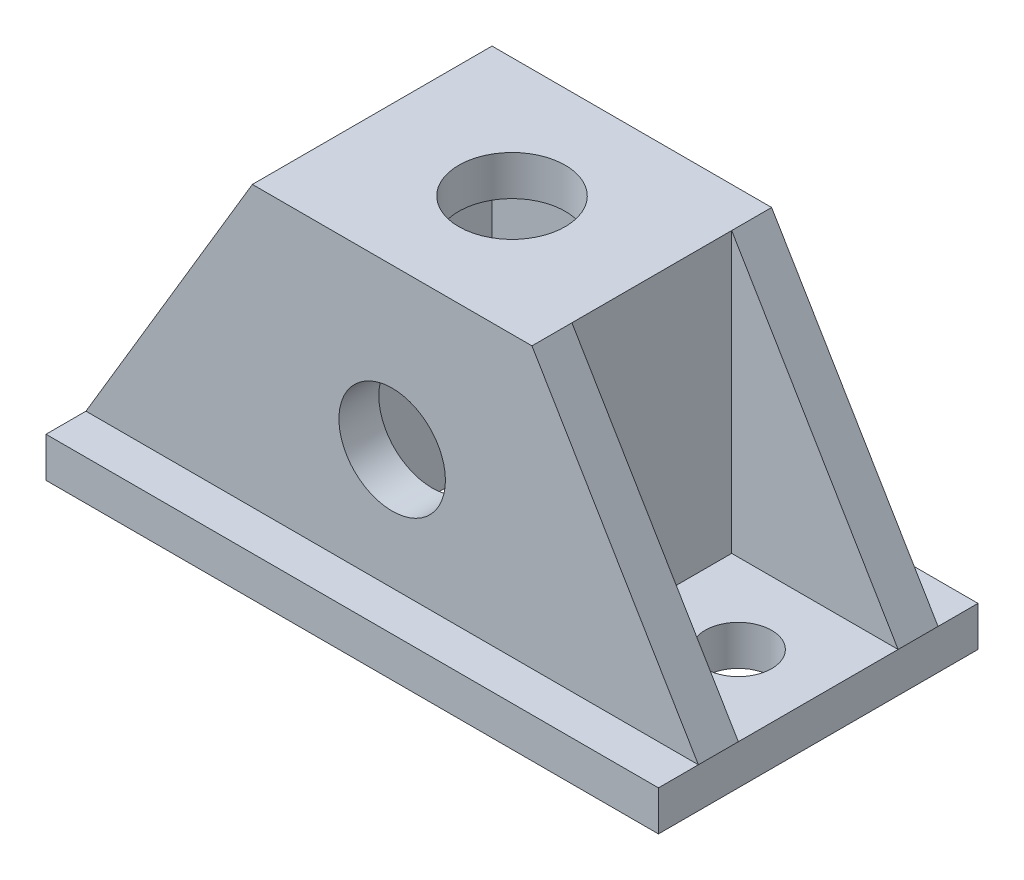
SolidWorks part; units mm, degrees
ref_plane "Piano frontale" through (0, 0, 0) normal (0, 0, 1) x (1, 0, 0)
ref_plane "Piano superiore" through (0, 0, 0) normal (0, 1, 0) x (1, 0, 0)
ref_plane "Piano destro" through (0, 0, 0) normal (1, 0, 0) x (0, 0, -1)
sketch "Schizzo1" plane through (0, 0, 0) normal (0, 1, 0) x (1, 0, 0)
  line L0 (0, -55) -> (0, 55) construction
  line L1 (-46, 24) -> (46, 24)
  line L2 (-46, 24) -> (-46, -24)
  line L3 (-46, -24) -> (46, -24)
  line L4 (46, 24) -> (46, -24)
  line L5 (-15, 12) -> (15, 12)
  line L6 (-15, 12) -> (-15, -12)
  line L7 (-15, -12) -> (15, -12)
  line L8 (15, 12) -> (15, -12)
  line L9 (-55, 0) -> (55, 0) construction
  point P8 (0, 12)
  point P11 (15, 0)
  point P14 (46, 0)
  point P15 (0, 24)
  dimension "D1" = 92
  dimension "D2" = 48
  dimension "D3" = 24
  dimension "D4" = 30
extrude "Estrusione-Estrusione1" add sketch "Schizzo1" along normal blind 6
sketch "Schizzo2" plane through (0, 6, 0) normal (0, 1, 0) x (1, 0, 0)
  line L0 (-3.3, 0) -> (3.3, 0) construction
  line L1 (-21, 18) -> (21, 18)
  line L2 (-21, 18) -> (-21, -18)
  line L3 (-21, -18) -> (21, -18)
  line L4 (21, 18) -> (21, -18)
  line L5 (0, -3.3) -> (0, 3.3) construction
  line L6 (15, -12) -> (15, 12) construction
  line L7 (-15, -12) -> (15, -12) construction
  line L8 (-15, 12) -> (-15, -12) construction
  line L9 (15, 12) -> (-15, 12) construction
  line L10 (15, -12) -> (15, 12)
  line L11 (-15, -12) -> (15, -12)
  line L12 (-15, 12) -> (-15, -12)
  line L13 (15, 12) -> (-15, 12)
  point P4 (-21, 0)
  point P7 (0, -18)
  dimension "D1" = 42
  dimension "D2" = 36
extrude "Estrusione-Estrusione2" add sketch "Schizzo2" along normal blind 36
sketch "Schizzo3" plane through (0, 42, 0) normal (0, 1, 0) x (1, 0, 0)
  line L0 (21, -18) -> (21, 18) construction
  line L1 (-21, -18) -> (21, -18) construction
  line L2 (-21, 18) -> (-21, -18) construction
  line L3 (21, 18) -> (-21, 18) construction
  line L4 (21, -18) -> (21, 18)
  line L5 (-21, -18) -> (21, -18)
  line L6 (-21, 18) -> (-21, -18)
  line L7 (21, 18) -> (-21, 18)
extrude "Estrusione-Estrusione3" add sketch "Schizzo3" along normal blind 6
sketch "Schizzo4" plane through (0, 0, 18) normal (0, 0, 1) x (1, 0, 0)
  line L0 (-21, 48) -> (-46, 6)
  line L1 (-46, 6) -> (-21, 6)
  line L2 (-21, 6) -> (-21, 48)
  line L3 (21, 48) -> (46, 6)
  line L4 (46, 6) -> (21, 6)
  line L5 (21, 6) -> (21, 48)
extrude "Estrusione-Estrusione4" add sketch "Schizzo4" against normal blind 6
mirror "Specchia1" about plane through (0, 0, 0) normal (0, 0, 1) of "Estrusione-Estrusione4"
hole_wizard "Foro Ø16.0 (16)-1" positions "Schizzo5" profile "Schizzo6" hole size "Ø16.0" standard "ISO" end condition through all
sketch "Schizzo5" plane through (0, 0, 18) normal (0, 0, 1) x (1, 0, 0)
  line L0 (-46, 0) -> (46, 0) construction
  line L1 (0, -26.4) -> (0, 26.4) construction
  point P0 (0, 24)
  point P5 (0, 0)
  dimension "D1" = 24
sketch "Schizzo6" plane through (0, 24, 18) normal (1, 0, 0) x (0, -1, 0)
  line L0 (0, 0) -> (0, 42)
  line L1 (0, 42) -> (8, 42)
  line L2 (8, 42) -> (8, 0)
  line L5 (8, 0) -> (0, 0)
  line L11 (0, -6.35) -> (0, 107.95) construction
  dimension "Thru Hole Dia." = 16
  dimension "Thru Hole Depth" = 42
hole_wizard "Foro Ø16.0 (16)-2" positions "Schizzo7" profile "Schizzo8" hole size "Ø16.0" standard "ISO" end condition through all
sketch "Schizzo7" plane through (0, 48, 0) normal (0, 1, 0) x (1, 0, 0)
  point P0 (0, 0)
sketch "Schizzo8" plane through (0, 48, 0) normal (1, 0, 0) x (0, 0, 1)
  line L0 (0, 0) -> (0, 48)
  line L1 (0, 48) -> (8, 48)
  line L2 (8, 48) -> (8, 0)
  line L5 (8, 0) -> (0, 0)
  line L11 (0, -6.35) -> (0, 107.95) construction
  dimension "Thru Hole Dia." = 16
  dimension "Thru Hole Depth" = 48
hole_wizard "Foro Ø10.0 (10)-1" positions "Schizzo9" profile "Schizzo10" hole size "Ø10.0" standard "ISO" end condition through all
sketch "Schizzo9" plane through (0, 6, 0) normal (0, 1, 0) x (1, 0, 0)
  line L0 (-26.4, 0) -> (26.4, 0) construction
  line L1 (-46, 12) -> (-46, -12) construction
  line L2 (46, -12) -> (46, 12) construction
  point P0 (-34, 0)
  point P4 (34, 0)
  dimension "D1" = 12
  dimension "D2" = 12
sketch "Schizzo10" plane through (-34, 6, 0) normal (1, 0, 0) x (0, 0, 1)
  line L0 (0, 0) -> (0, 6)
  line L1 (0, 6) -> (5, 6)
  line L2 (5, 6) -> (5, 0)
  line L5 (5, 0) -> (0, 0)
  line L11 (0, -6.35) -> (0, 107.95) construction
  dimension "Thru Hole Dia." = 10
  dimension "Thru Hole Depth" = 6
equation "\"D2@Schizzo9\"=\"D1@Schizzo9\""
